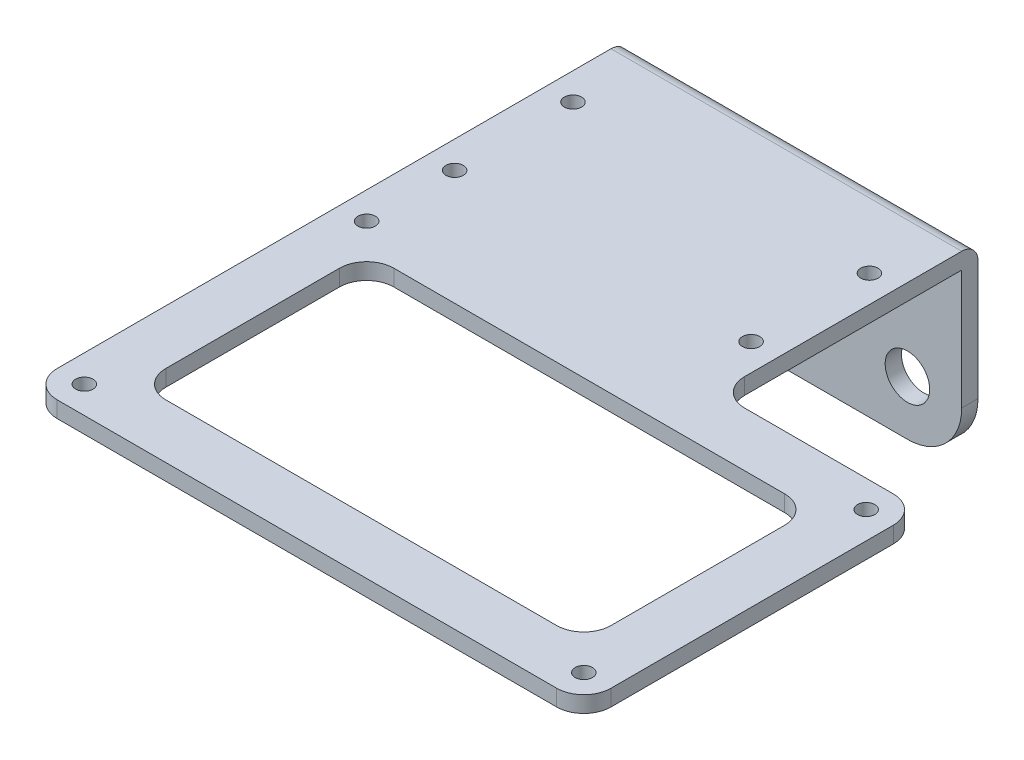
SolidWorks part; units mm, degrees
ref_plane "前视基准面" through (0, 0, 0) normal (0, 0, 1) x (1, 0, 0)
ref_plane "上视基准面" through (0, 0, 0) normal (0, 1, 0) x (1, 0, 0)
ref_plane "右视基准面" through (0, 0, 0) normal (1, 0, 0) x (0, 0, -1)
other "Configuration Table"
sketch "草图1" plane through (0, 0, 0) normal (0, 1, 0) x (1, 0, 0)
  line L1 (-55, 55) -> (55, 55)
  line L2 (-55, 55) -> (-55, -55)
  line L3 (-55, -55) -> (55, -55)
  line L4 (55, 55) -> (55, -55)
  line L5 (-55, 55) -> (55, -55) construction
  line L6 (-55, -55) -> (55, 55) construction
  point P0 (0, 0)
  dimension "D1" = 110
  dimension "D2" = 110
extrude "凸台-拉伸1" add sketch "草图1" along normal blind 3
sketch "草图2" plane through (0, 3, 0) normal (0, 1, 0) x (1, 0, 0)
  line L0 (-55, 55) -> (-55, -55) construction
  line L1 (55, 55) -> (-55, 55) construction
  line L2 (-55, -55) -> (55, -55) construction
  circle A0 centre (-50, 40) radius 1.6
  circle A1 centre (4.6, 40) radius 1.6
  circle A2 centre (4.6, 18.2) radius 1.6
  circle A3 centre (-50, 18.2) radius 1.6
  circle A4 centre (-50, -50) radius 1.6
  circle A5 centre (42, -50) radius 1.6
  circle A6 centre (42, 2) radius 1.6
  circle A7 centre (-50, 2) radius 1.6
  dimension "D1" = 3.2
  dimension "D3" = 15
  dimension "D6" = 3.2
  dimension "D7" = 5
  dimension "D11" = 52
  dimension "D12" = 92
  dimension "D13" = 21.8
  dimension "D14" = 54.6
  dimension "D2" = 5
  dimension "D8" = 5
  dimension "D4" = 2
  dimension "D5" = 2
  dimension "D9" = 2
  dimension "D10" = 2
extrude "切除-拉伸1" cut sketch "草图2" against normal up to next
sketch "草图3" plane through (0, 3, 0) normal (0, 1, 0) x (1, 0, 0)
  line L0 (55, 17) -> (55, -55)
  line L1 (55, 55) -> (9.6, 55)
  line L2 (55, 55) -> (55, 17)
  line L3 (47, 7) -> (9.6, 7)
  line L4 (9.6, 55) -> (9.6, 7)
  line L6 (55, -55) -> (47, -55)
  line L7 (-55, -55) -> (55, -55) construction
  line L8 (47, -55) -> (47, 7)
  circle A1 centre (4.6, 40) radius 1.6 construction
  circle A2 centre (42, 2) radius 1.6 construction
  circle A4 centre (42, -50) radius 1.6 construction
  dimension "D1" = 5
  dimension "D2" = 5
  dimension "D3" = 5
extrude "切除-拉伸2" cut sketch "草图3" against normal up to next
sketch "草图5" plane through (0, 0, 0) normal (0, -1, 0) x (1, 0, 0)
  line L0 (-55, -55) -> (-55, 55) construction
  line L1 (9.6, -55) -> (-55, -55)
  line L2 (9.6, -55) -> (9.6, -52)
  line L3 (9.6, -52) -> (-55, -52)
  line L4 (-55, -55) -> (-55, -52)
  dimension "D1" = 3
  dimension "D2" = 64.6
extrude "凸台-拉伸2" add sketch "草图5" along normal blind 32
sketch "草图6" plane through (0, 0, -55) normal (0, 0, -1) x (-1, 0, 0)
  line L0 (-9.6, -22) -> (55, -22) construction
  line L5 (-9.6, 0) -> (55, 0) construction
  line L6 (-9.6, 0) -> (-9.6, -32) construction
  line L7 (-9.6, -32) -> (55, -32) construction
  line L8 (55, 0) -> (55, -32) construction
  circle A4 centre (0.4, -22) radius 4.1
  circle A5 centre (45, -22) radius 4.1
  dimension "D2" = 10
  dimension "D3" = 8.2
  dimension "D4" = 8.2
  dimension "D5" = 10
  dimension "D6" = 10
  dimension "D7" = 44.6
  dimension "D1" = 32
extrude "切除-拉伸3" cut sketch "草图6" against normal up to next
sketch "草图7" plane through (0, 3, 0) normal (0, 1, 0) x (1, 0, 0)
  line L0 (-50, 2) -> (42, -50) construction
  line L1 (-50, 2) -> (42, 2) construction
  line L2 (-50, 2) -> (-50, -50) construction
  line L3 (-50, -50) -> (42, -50) construction
  line L4 (42, 2) -> (42, -50) construction
  line L5 (-50, 40) -> (4.6, 40) construction
  line L6 (-50, 40) -> (-50, 18.2) construction
  line L7 (-50, 18.2) -> (4.6, 18.2) construction
  line L8 (4.6, 40) -> (4.6, 18.2) construction
  line L9 (-50, -50) -> (42, 2) construction
  line L10 (-50, 40) -> (4.6, 18.2) construction
  line L11 (-40, -3) -> (32, -3)
  line L12 (-45, -8) -> (-45, -40)
  line L13 (-40, -45) -> (32, -45)
  line L14 (37, -8) -> (37, -40)
  line L15 (-45, -3) -> (37, -45) construction
  line L16 (-45, -45) -> (37, -3) construction
  line L17 (4.6, 40) -> (-50, 18.2) construction
  circle A0 centre (-50, 2) radius 1.6 construction
  circle A1 centre (42, 2) radius 1.6 construction
  arc A2 (32, -3) -> (37, -8) centre (32, -8) cw
  arc A3 (32, -45) -> (37, -40) centre (32, -40) ccw
  arc A4 (-45, -40) -> (-40, -45) centre (-40, -40) ccw
  arc A5 (-40, -3) -> (-45, -8) centre (-40, -8) ccw
  point P12 (-4, -24)
  dimension "D5" = 5
  dimension "D1" = 5
  dimension "D2" = 5
  dimension "D3" = 42
  dimension "D4" = 82
extrude "切除-拉伸4" cut sketch "草图7" against normal up to next
fillet "圆角1" radius 5 4 edges at (9.6, 1.5, -7) (47, 1.5, -7) (47, 1.5, 55) (-55, 1.5, 55)
fillet "圆角2" radius 3 1 edges at (-22.7, 3, -55)
fillet "圆角3" radius 10 2 edges at (-55, -32, -53.5) (9.6, -32, -53.5)
